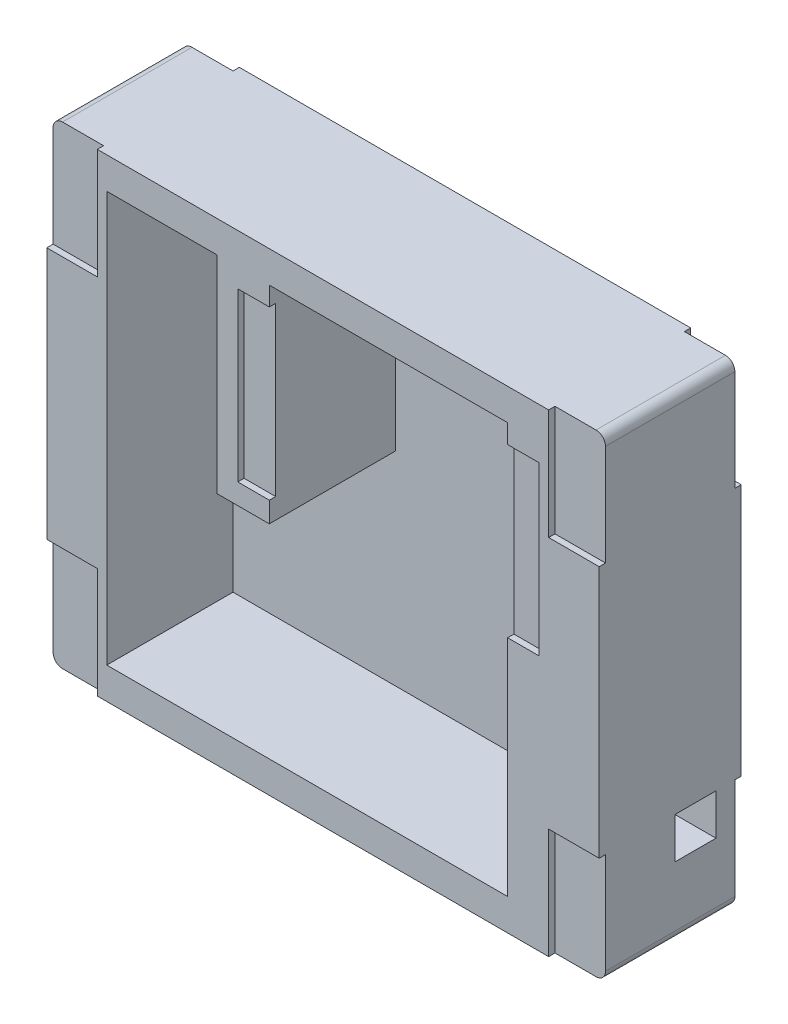
SolidWorks part; units mm, degrees
ref_plane "Front Plane" through (0, 0, 0) normal (0, 0, 1) x (1, 0, 0)
ref_plane "Top Plane" through (0, 0, 0) normal (0, 1, 0) x (1, 0, 0)
ref_plane "Right Plane" through (0, 0, 0) normal (1, 0, 0) x (0, 0, -1)
sketch "Sketch2" plane through (0, 0, 0) normal (0, 0, 1) x (1, 0, 0)
  line L1 (0, 0) -> (-175, 0)
  line L2 (0, 0) -> (0, -150)
  line L3 (0, -150) -> (-175, -150)
  line L4 (-175, 0) -> (-175, -150)
  dimension "D1" = 175
  dimension "D2" = 150
extrude "Boss-Extrude1" add sketch "Sketch2" along normal blind 45
sketch "Sketch3" plane through (0, 0, 45) normal (0, 0, 1) x (1, 0, 0)
  line L0 (0, 0) -> (-175, 0) construction
  line L1 (-104.5, -10) -> (-29, -10)
  line L2 (-104.5, -10) -> (-104.5, -100)
  line L4 (-29, -10) -> (-29, -140)
  line L5 (-156, -140) -> (-29, -140)
  line L6 (-175, -150) -> (0, -150) construction
  line L8 (-175, 0) -> (-175, -150) construction
  line L9 (0, -150) -> (0, 0) construction
  line L10 (-156, -100) -> (-104.5, -100)
  line L11 (-156, -100) -> (-156, -140)
  dimension "D1" = 10
  dimension "D2" = 75.5
  dimension "D3" = 10
  dimension "D4" = 29
  dimension "D5" = 19
  dimension "D7" = 100
extrude "Cut-Extrude1" cut sketch "Sketch3" against normal blind 40
sketch "Sketch5" plane through (0, 0, 0) normal (1, 0, 0) x (0, 0, -1)
  line L0 (-45, -150) -> (0, -150) construction
  line L1 (-21, -115) -> (-8, -115)
  line L2 (-21, -115) -> (-21, -128)
  line L3 (-21, -128) -> (-8, -128)
  line L4 (-8, -115) -> (-8, -128)
  line L6 (-45, -150) -> (-45, 0) construction
  point P4 (-14.5, -128)
  dimension "D1" = 22
  dimension "D2" = 13
  dimension "D3" = 13
  dimension "D4" = 24
extrude "Cut-Extrude3" cut sketch "Sketch5" against normal blind 50
sketch "Sketch6" plane through (0, 0, 45) normal (0, 0, 1) x (1, 0, 0)
  line L0 (-104.5, -10) -> (-104.5, -100) construction
  line L1 (-114.5, -16) -> (-104.5, -16)
  line L2 (-114.5, -16) -> (-114.5, -69)
  line L3 (-114.5, -69) -> (-104.5, -69)
  line L4 (-104.5, -16) -> (-104.5, -69)
  line L5 (-29, -140) -> (-29, -10) construction
  line L6 (-29, -16) -> (-19, -16)
  line L7 (-29, -16) -> (-29, -69)
  line L8 (-29, -69) -> (-19, -69)
  line L9 (-19, -16) -> (-19, -69)
  line L10 (0, 0) -> (-175, 0) construction
  point P12 (-109.5, -16)
  dimension "D1" = 53
  dimension "D2" = 53
  dimension "D3" = 16
  dimension "D4" = 16
  dimension "D5" = 10
  dimension "D6" = 10
extrude "Cut-Extrude4" cut sketch "Sketch6" against normal blind 2
sketch "Sketch7" plane through (0, 0, 45) normal (0, 0, 1) x (1, 0, 0)
  line L0 (0, 0) -> (-175, 0) construction
  line L1 (-156, -10) -> (-121, -10)
  line L2 (-156, -10) -> (-156, -140)
  line L3 (-156, -140) -> (-121, -140)
  line L4 (-121, -10) -> (-121, -140)
  line L5 (-175, 0) -> (-175, -150) construction
  line L7 (-175, -150) -> (0, -150) construction
  dimension "D1" = 10
  dimension "D2" = 35
  dimension "D3" = 19
  dimension "D4" = 10
extrude "Cut-Extrude5" cut sketch "Sketch7" against normal blind 40
sketch "Sketch9" plane through (0, 0, 45) normal (0, 0, 1) x (1, 0, 0)
  line L1 (-175, 0) -> (-159, 0)
  line L2 (-175, 0) -> (-175, -35)
  line L3 (-175, -35) -> (-159, -35)
  line L4 (-159, 0) -> (-159, -35)
  line L5 (-175, -150) -> (-159, -150)
  line L6 (-175, -150) -> (-175, -115)
  line L7 (-175, -115) -> (-159, -115)
  line L8 (-159, -150) -> (-159, -115)
  line L9 (0, -150) -> (-16, -150)
  line L10 (0, -150) -> (0, -115)
  line L11 (0, -115) -> (-16, -115)
  line L12 (-16, -150) -> (-16, -115)
  line L13 (0, 0) -> (-16, 0)
  line L14 (0, 0) -> (0, -35)
  line L15 (0, -35) -> (-16, -35)
  line L16 (-16, 0) -> (-16, -35)
  dimension "D1" = 16
  dimension "D2" = 35
extrude "Cut-Extrude6" cut sketch "Sketch9" against normal blind 2
sketch "Sketch10" plane through (0, 0, 45) normal (0, 0, 1) x (1, 0, 0)
  line L0 (-104.5, -69) -> (-104.5, -100) construction
  line L1 (-121, -100) -> (-104.5, -100)
  line L2 (-121, -100) -> (-121, -75.5)
  line L3 (-121, -75.5) -> (-104.5, -75.5)
  line L4 (-104.5, -100) -> (-104.5, -75.5)
  dimension "D1" = 24.5
extrude "Cut-Extrude7" cut sketch "Sketch10" against normal blind 40
sketch "Sketch11" plane through (0, 0, 0) normal (0, 0, -1) x (-1, 0, 0)
  line L1 (0, 0) -> (16, 0)
  line L2 (0, 0) -> (0, -35)
  line L3 (0, -35) -> (16, -35)
  line L4 (16, 0) -> (16, -35)
  line L5 (0, -150) -> (16, -150)
  line L6 (0, -150) -> (0, -115)
  line L7 (0, -115) -> (16, -115)
  line L8 (16, -150) -> (16, -115)
  line L9 (175, -150) -> (159, -150)
  line L10 (175, -150) -> (175, -115)
  line L11 (175, -115) -> (159, -115)
  line L12 (159, -150) -> (159, -115)
  line L13 (175, 0) -> (159, 0)
  line L14 (175, 0) -> (175, -35)
  line L15 (175, -35) -> (159, -35)
  line L16 (159, 0) -> (159, -35)
  dimension "D1" = 35
  dimension "D2" = 16
extrude "Cut-Extrude8" cut sketch "Sketch11" against normal blind 2
fillet "Fillet1" radius 3 4 edges at (-175, -150, 22.5) (0, -150, 22.5) (0, 0, 22.5) (-175, 0, 22.5)
